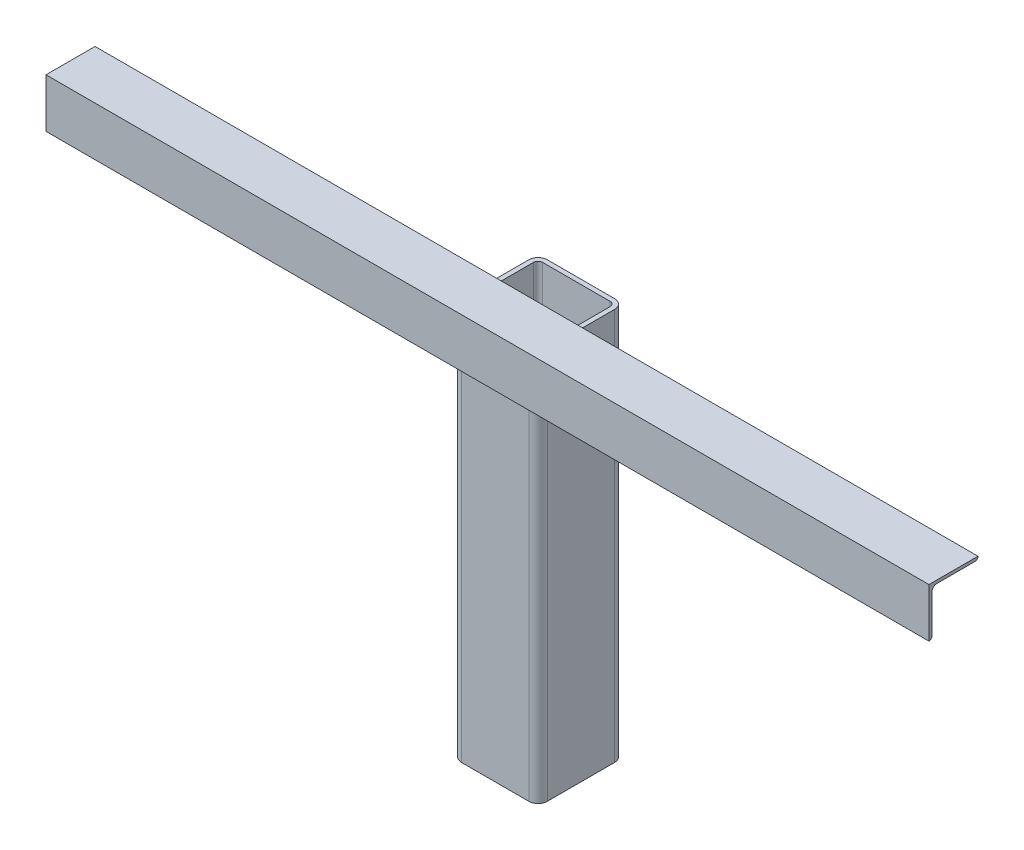
SolidWorks part; units mm, degrees
material "Plain Carbon Steel"
ref_plane "Front" through (0, 0, 0) normal (0, 0, 1) x (1, 0, 0)
ref_plane "Top" through (0, 0, 0) normal (0, 1, 0) x (1, 0, 0)
ref_plane "Right" through (0, 0, 0) normal (1, 0, 0) x (0, 0, -1)
sketch3d "3DSketch2"
  line L0 (0, 0, 0) -> (0, 406.4, 0)
  line L1 (457.2, 406.4, 0) -> (-457.2, 406.4, 0)
  dimension "D1" = 914.4
other "vertical"
ref_plane "Plane2" through (0, 0, 0) normal (0, 1, 0) x (1, 0, 0)
sketch "Sketch12" plane through (0, 0, -44.45) normal (0, 1, 0) x (1, 0, 0)
  line L0 (-34.925, -39.6875) -> (34.925, -39.6875)
  line L1 (-39.6875, -34.925) -> (-39.6875, 34.925)
  line L2 (34.925, 39.6875) -> (-34.925, 39.6875)
  line L3 (39.6875, 34.925) -> (39.6875, -34.925)
  line L4 (-34.925, -44.45) -> (34.925, -44.45)
  line L5 (-44.45, -34.925) -> (-44.45, 34.925)
  line L6 (34.925, 44.45) -> (-34.925, 44.45)
  line L7 (44.45, 34.925) -> (44.45, -34.925)
  line L8 (0, 0) -> (39.6875, 0) construction
  line L9 (0, 0) -> (0, 39.6875) construction
  arc A0 (44.45, 34.925) -> (34.925, 44.45) centre (34.925, 34.925) ccw
  arc A1 (34.925, -44.45) -> (44.45, -34.925) centre (34.925, -34.925) ccw
  arc A2 (-44.45, -34.925) -> (-34.925, -44.45) centre (-34.925, -34.925) ccw
  arc A3 (-34.925, 44.45) -> (-44.45, 34.925) centre (-34.925, 34.925) ccw
  arc A4 (-34.925, 39.6875) -> (-39.6875, 34.925) centre (-34.925, 34.925) ccw
  arc A5 (39.6875, 34.925) -> (34.925, 39.6875) centre (34.925, 34.925) ccw
  arc A6 (34.925, -39.6875) -> (39.6875, -34.925) centre (34.925, -34.925) ccw
  arc A7 (-39.6875, -34.925) -> (-34.925, -39.6875) centre (-34.925, -34.925) ccw
  point P3 (0, 44.45)
  point P4 (44.45, 0)
  point P5 (0, -44.45)
  point P6 (-44.45, 0)
  point P7 (-44.45, 44.45)
  point P8 (-44.45, -44.45)
  point P33 (0, 0)
  point P35 (44.45, -44.45)
  point P36 (44.45, 44.45)
  point P37 (0, 0)
  dimension "D1" = 9.525
  dimension "Thickness" = 4.7625
  dimension "V_leg" = 88.9
other "crossbar"
ref_plane "Plane3" through (457.2, 406.4, 0) normal (-1, 0, 0) x (0, 0, -1)
sketch "Sketch13" plane through (457.2, 409.575, 7.9375) normal (-1, 0, 0) x (0, 0, -1)
  line L0 (0, 0) -> (0, 50.8)
  line L1 (0, 50.8) -> (0.0051, 50.8)
  line L2 (3.175, 47.6301) -> (3.175, 7.9375)
  line L3 (7.9375, 3.175) -> (47.6301, 3.175)
  line L4 (50.8, 0.0051) -> (50.8, 0)
  line L5 (50.8, 0) -> (0, 0)
  arc A0 (50.8, 0.0051) -> (47.6301, 3.175) centre (47.6301, 0.0051) ccw
  arc A1 (0.0051, 50.8) -> (3.175, 47.6301) centre (0.0051, 47.6301) cw
  arc A2 (7.9375, 3.175) -> (3.175, 7.9375) centre (7.9375, 7.9375) cw
  point P10 (25.4, 0)
  point P14 (0, 25.4)
  point P15 (3.175, 25.4)
  point P16 (25.4, 3.175)
  point P17 (3.175, 50.8)
  point P18 (50.8, 3.175)
  point P19 (0, 0)
  dimension "D2" = 0.0051
  dimension "Radius_1" = 4.7625
  dimension "D1" = 3.175
  dimension "H_leg" = 50.8
